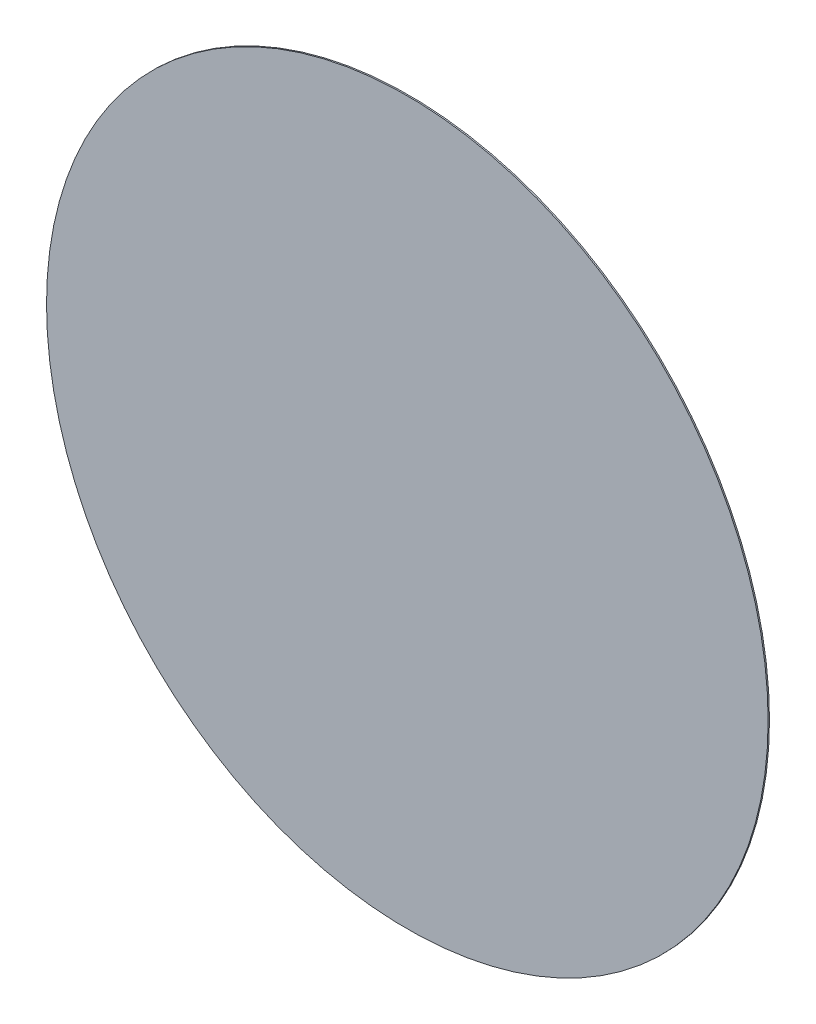
SolidWorks part; units mm, degrees
material "Homopolymère PP"
ref_plane "Plan de face" through (0, 0, 0) normal (0, 0, 1) x (1, 0, 0)
ref_plane "Plan de dessus" through (0, 0, 0) normal (0, 1, 0) x (1, 0, 0)
ref_plane "Plan de droite" through (0, 0, 0) normal (1, 0, 0) x (0, 0, -1)
sketch "Esquisse1" plane through (0, 0, 0) normal (0, 0, 1) x (1, 0, 0)
  circle A0 centre (0, 0) radius 13.3
  dimension "D1" = 26.6
extrude "Boss.-Extru.1" add sketch "Esquisse1" along normal blind 0.05
